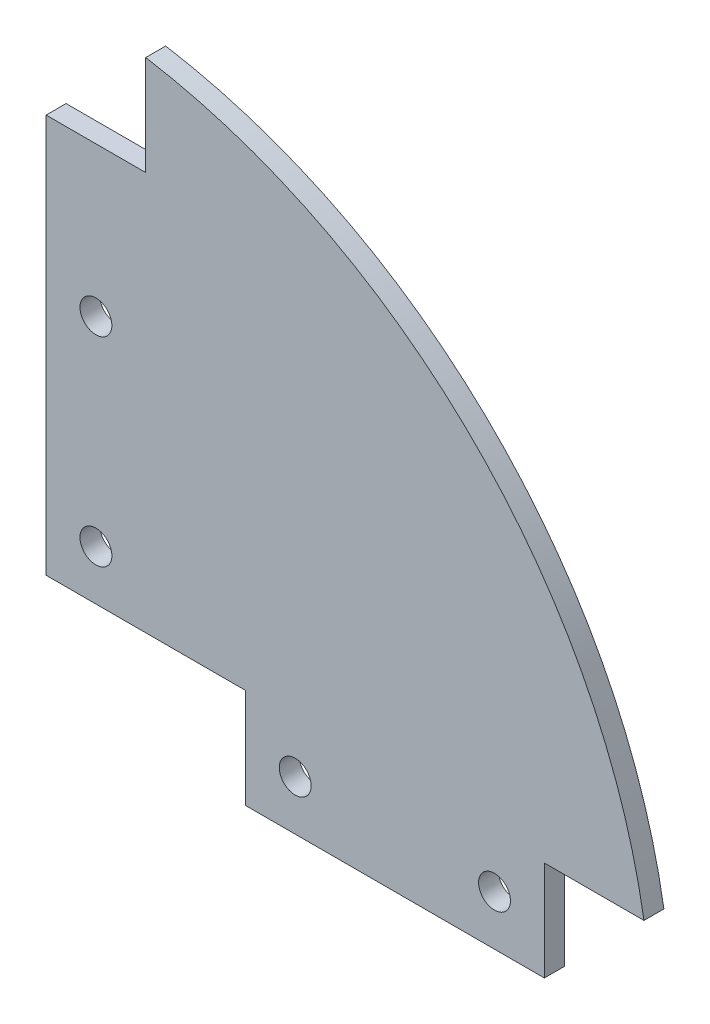
SolidWorks part; units mm, degrees
ref_plane "正面" through (0, 0, 0) normal (0, 0, 1) x (1, 0, 0)
ref_plane "平面" through (0, 0, 0) normal (0, 1, 0) x (1, 0, 0)
ref_plane "右側面" through (0, 0, 0) normal (1, 0, 0) x (0, 0, -1)
sketch "ｽｹｯﾁ1" plane through (0, 0, 0) normal (0, 0, 1) x (1, 0, 0)
  line L0 (0, 0) -> (20, 0) construction
  line L1 (20, 0) -> (0, 10) construction
  line L2 (0, 10) -> (0, 0) construction
  line L3 (20, 0) -> (50, 0)
  line L4 (50, 0) -> (50, 10)
  line L5 (50, 10) -> (60, 10)
  line L6 (10, 60) -> (10, 50)
  line L7 (10, 50) -> (0, 50)
  line L8 (0, 50) -> (0, 10)
  line L9 (0, 10) -> (20, 10)
  line L10 (20, 10) -> (20, 0)
  line L11 (5, 50) -> (5, 9.6887) construction
  line L12 (20, 5) -> (50, 5) construction
  arc A0 (60, 10) -> (10, 60) centre (0, 0) ccw
  circle A1 centre (5, 35) radius 1.6
  circle A2 centre (5, 15) radius 1.6
  circle A3 centre (25, 5) radius 1.6
  circle A4 centre (45, 5) radius 1.6
  point P23 (20, 5)
  point P24 (0, 0)
  point P25 (0, 0)
  dimension "D8" = 20
  dimension "D9" = 5
  dimension "D10" = 3.2
  dimension "D11" = 5
  dimension "D12" = 20
  dimension "D1" = 20
  dimension "D2" = 10
  dimension "D3" = 30
  dimension "D4" = 10
  dimension "D5" = 10
  dimension "D6" = 10
  dimension "D7" = 10
extrude "ﾎﾞｽ - 押し出し1" add sketch "ｽｹｯﾁ1" along normal blind 2
